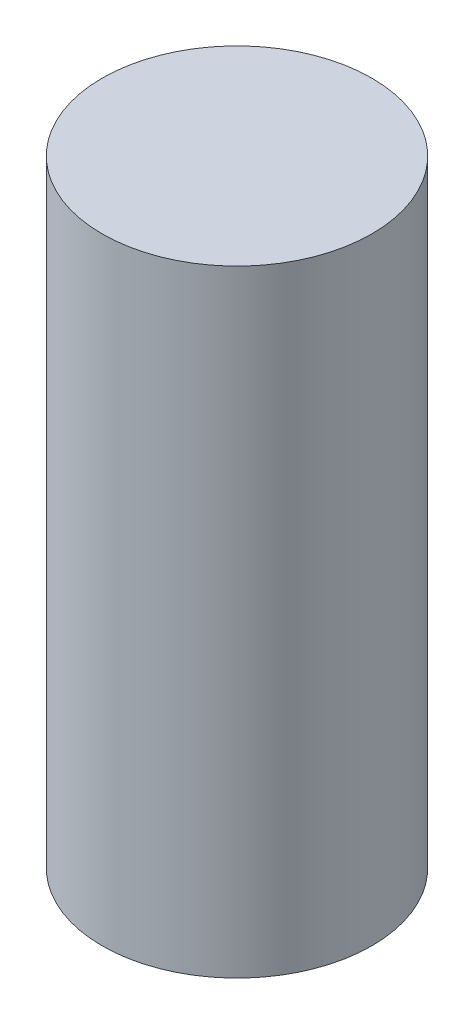
SolidWorks part; units mm, degrees
ref_plane "前视基准面" through (0, 0, 0) normal (0, 0, 1) x (1, 0, 0)
ref_plane "上视基准面" through (0, 0, 0) normal (0, 1, 0) x (1, 0, 0)
ref_plane "右视基准面" through (0, 0, 0) normal (1, 0, 0) x (0, 0, -1)
other "Configuration Table"
sketch "草图1" plane through (0, 0, 0) normal (0, 1, 0) x (1, 0, 0)
  circle A0 centre (0, 0) radius 7
extrude "凸台-拉伸1" add sketch "草图1" along normal blind 32
